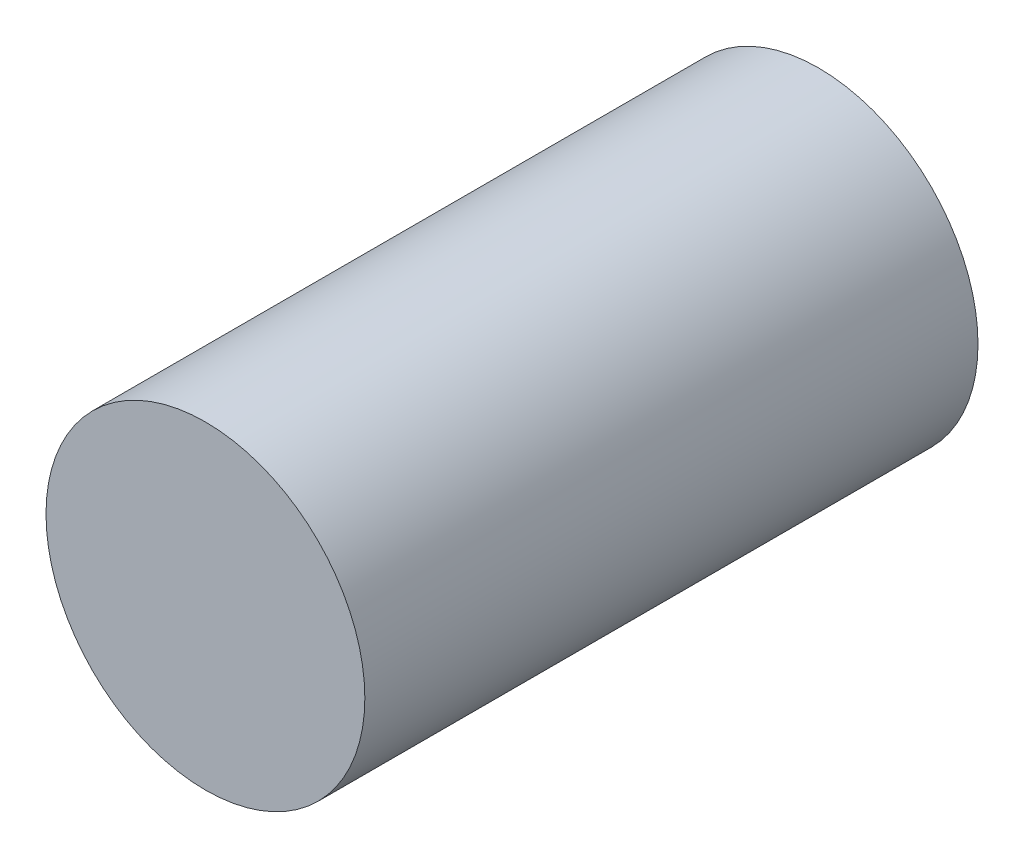
SolidWorks part; units mm, degrees
ref_plane "Front Plane" through (0, 0, 0) normal (0, 0, 1) x (1, 0, 0)
ref_plane "Top Plane" through (0, 0, 0) normal (0, 1, 0) x (1, 0, 0)
ref_plane "Right Plane" through (0, 0, 0) normal (1, 0, 0) x (0, 0, -1)
sketch "Sketch1" plane through (0, 0, 0) normal (0, 0, 1) x (1, 0, 0)
  circle A0 centre (0, 0) radius 13
extrude "Boss-Extrude1" add sketch "Sketch1" along normal blind 50
